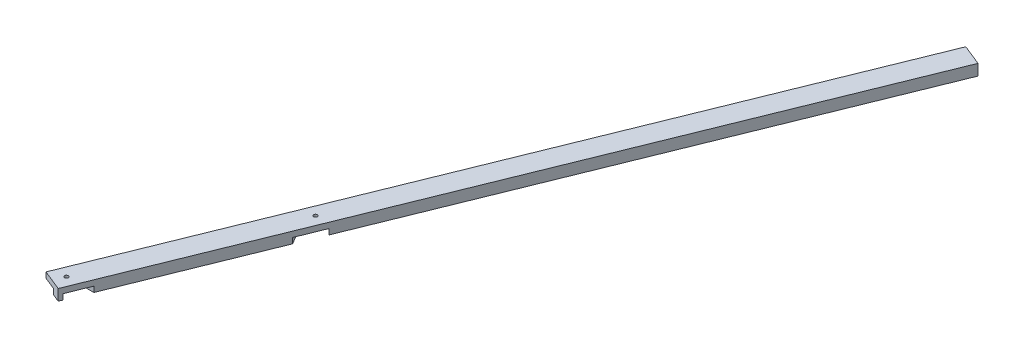
SolidWorks part; units mm, degrees
ref_plane "Front Plane" through (0, 0, 0) normal (0, 0, 1) x (1, 0, 0)
ref_plane "Top Plane" through (0, 0, 0) normal (0, 1, 0) x (1, 0, 0)
ref_plane "Right Plane" through (0, 0, 0) normal (1, 0, 0) x (0, 0, -1)
sketch "Sketch2" plane through (0, 0, 0) normal (0, 1, 0) x (1, 0, 0)
  line L0 (0, 0) -> (0, -38.1)
  line L1 (0, -38.1) -> (-1219.2, -38.1)
  line L2 (-1219.2, -38.1) -> (-1219.2, 0)
  line L3 (-1219.2, 0) -> (0, 0)
  line L4 (-323.85, -19.05) -> (-19.05, -19.05)
  line L5 (-19.05, -19.05) -> (-200.025, 287.0536)
  line L6 (-200.025, 287.0536) -> (-323.85, -19.05)
  line L7 (-323.85, -19.05) -> (-341.5098, -11.9062)
  line L8 (-323.85, -19.05) -> (-306.1902, -26.1937)
  line L9 (-341.5098, -11.9062) -> (-348.6536, -29.5661)
  line L10 (-306.1902, -26.1937) -> (-311.0065, -38.1)
  line L11 (-348.6536, -29.5661) -> (-313.3339, -43.8536)
  line L12 (108.5464, 1100.6626) -> (143.8661, 1086.3751)
  line L13 (143.8661, 1086.3751) -> (-295.5943, 0)
  line L14 (-341.5098, -11.9062) -> (108.5464, 1100.6626)
  line L15 (-200.025, 287.0536) -> (-183.6266, 296.7487)
  line L16 (-183.6266, 296.7487) -> (-193.3217, 313.1471)
  line L17 (-193.3217, 313.1471) -> (-226.1185, 293.7569)
  line L18 (-226.1185, 293.7569) -> (-52.4431, 0)
  line L19 (394.3672, -755.7411) -> (427.164, -736.3509)
  line L20 (427.164, -736.3509) -> (0, -13.8399)
  line L21 (-303.3004, -19.05) -> (-306.1902, -26.1937)
  line L22 (-8.1824, 0) -> (-183.6266, 296.7487)
  line L23 (-29.9176, -38.1) -> (394.3672, -755.7411)
  line L24 (-29.9176, -38.1) -> (-52.4431, 0)
  line L25 (0, -13.8399) -> (-8.1824, 0)
  line L26 (-303.3004, -19.05) -> (-295.5943, 0)
  line L27 (-313.3339, -43.8536) -> (-311.0065, -38.1)
  circle A0 centre (-19.05, -19.05) radius 3.175
  circle A1 centre (-323.85, -19.05) radius 3.175
  circle A2 centre (-200.025, 287.0536) radius 3.175
  point P22 (0, 730.7286)
  dimension "D5" = 6.35
  dimension "D6" = 6.35
  dimension "D18" = 6.35
  dimension "D1" = 38.1
  dimension "D2" = 1219.2
  dimension "D3" = 19.05
  dimension "D4" = 19.05
  dimension "D7" = 304.8
  dimension "D8" = 19.05
  dimension "D9" = 330.2
  dimension "D10" = 355.6
  dimension "D11" = 90
  dimension "D12" = 19.05
  dimension "D13" = 90
  dimension "D14" = 19.05
  dimension "D15" = 19.05
  dimension "D16" = 19.05
  dimension "D19" = 90
  dimension "D20" = 19.05
  dimension "D21" = 19.05
  dimension "D22" = 38.1
  dimension "D23" = 1219.2
  dimension "D24" = 38.1
  dimension "D25" = 67.976
  dimension "D26" = 295.5943
  dimension "D27" = 311.0065
  dimension "D28" = 8.1824
  dimension "D29" = 29.9176
  dimension "D30" = 52.4431
  dimension "D17" = 1219.2
extrude "Boss-Extrude3" add sketch "Sketch2" along normal blind 19.05 contours L18 L14 L3 L6 | L18 L6 L3 L13 | A1 L6 L3 L14 L7 | A1 L4 L26 L3 L6 | A1 L7 L9 L11 L1 L10 L8 | A1 L8 L21 L4 | L11 L27 L1 | L22 L13 L12 L14 L17 L16 | A2 L6 L18 L13 L5 | A2 L15 L16 L17 L14 L18 L6 | A2 L5 L13 L22 L15
sketch "Sketch6" plane through (0, 0, 0) normal (0, -1, 0) x (1, 0, 0)
  line L0 (-348.6536, 29.5661) -> (-313.3339, 43.8536)
  line L1 (-313.3339, 43.8536) -> (-311.0065, 38.1)
  line L2 (-311.0065, 38.1) -> (-342.9923, 38.1)
  line L3 (0, 38.1) -> (-1219.2, 38.1) construction
  line L4 (-295.5943, 0) -> (-311.0065, 38.1)
  line L5 (-295.5943, 0) -> (-346.1771, 0)
  line L6 (-1219.2, 0) -> (0, 0) construction
  line L7 (-348.6536, 29.5661) -> (-333.5031, -7.887)
  line L8 (-341.5098, 11.9062) -> (108.5464, -1100.6626) construction
  point P17 (-336.6935, 0)
  line M2 (-348.6536, 29.5661) -> (108.5464, -1100.6626)
  line M4 (143.8661, -1086.3751) -> (-313.3339, 43.8536)
  circle M5 centre (-323.85, 19.05) radius 3.175
extrude "Cut-Extrude3" cut sketch "Sketch6" against normal blind 9.525 contours L5 L2 L0 M4 M2 M5
sketch "Sketch7" plane through (0, 0, 0) normal (0, -1, 0) x (1, 0, 0)
  line L0 (-196.8141, -244.1911) -> (-221.2168, -285.4661)
  line L1 (143.8661, -1086.3751) -> (-295.5943, 0) construction
  line L2 (-226.1185, -293.7569) -> (-52.4431, 0) construction
  line L3 (-341.5098, 11.9062) -> (108.5464, -1100.6626) construction
  line L4 (-221.2168, -285.4661) -> (-215.268, -300.172)
  line L5 (-193.3217, -313.1471) -> (-226.1185, -293.7569) construction
  line L6 (-215.268, -300.172) -> (-193.3217, -313.1471)
  line L7 (-193.3217, -313.1471) -> (-178.8332, -288.6411)
  line L8 (-8.1824, 0) -> (-183.6266, -296.7487) construction
  line L9 (-178.8332, -288.6411) -> (-196.8141, -244.1911)
extrude "Cut-Extrude4" cut sketch "Sketch7" against normal blind 9.525
